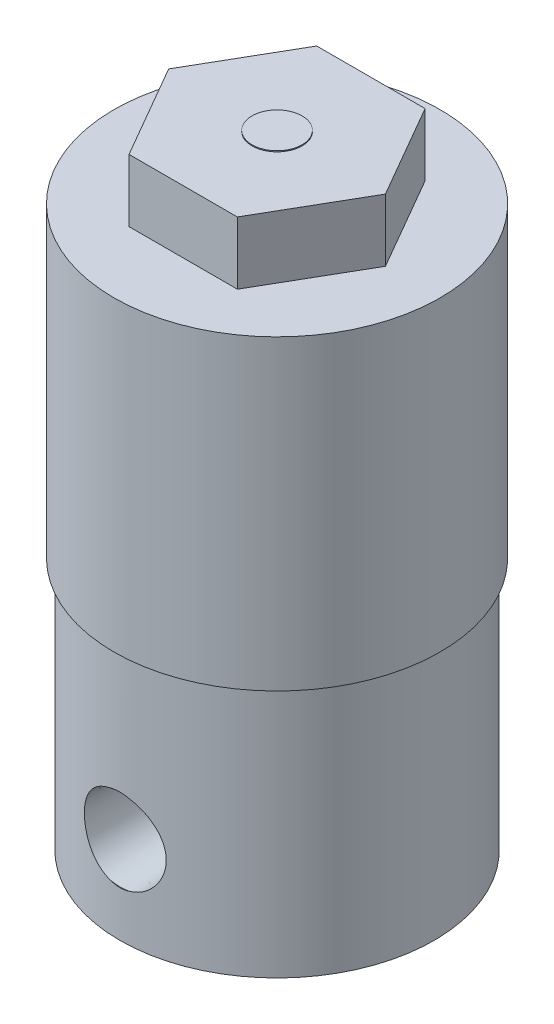
SolidWorks part; units mm, degrees
ref_plane "Plan de face" through (0, 0, 0) normal (0, 0, 1) x (1, 0, 0)
ref_plane "Plan de dessus" through (0, 0, 0) normal (0, 1, 0) x (1, 0, 0)
ref_plane "Plan de droite" through (0, 0, 0) normal (1, 0, 0) x (0, 0, -1)
sketch "Esquisse1" plane through (0, 0, 0) normal (0, 1, 0) x (1, 0, 0)
  circle A0 centre (0, 0) radius 12.56
extrude "Boss.-Extru.1" add sketch "Esquisse1" along normal blind 20.19 contours A0
ref_plane "Plan1" through (0, 0, 12.56) normal (0, 0, 1) x (1, 0, 0)
hole_wizard "Trou taraudé 1/8 Rc1" positions "Esquisse8" profile "Esquisse9" size "1/8" standard "KS"
sketch "Esquisse8" plane through (0, 0, 12.56) normal (0, 0, 1) x (1, 0, 0)
  line L0 (0, -11.1045) -> (0, 11.1045) construction
  line L1 (13.816, 0) -> (-13.816, 0) construction
  point P0 (0, 6.96)
  dimension "D1" = 6.96
sketch "Esquisse9" plane through (0, 6.96, 12.56) normal (1, 0, 0) x (0, -1, 0)
  line L0 (0, 0) -> (0, 10.8734)
  line L1 (3.95, 8.5) -> (0, 10.8734)
  line L2 (-3.95, 8.5) -> (0, 10.8734) construction
  line L3 (3.95, 8.5) -> (3.95, 7.4)
  line L4 (3.95, 7.4) -> (3.0528, 7.4)
  line L5 (3.0528, 7.4) -> (3.283, 0.025)
  line L6 (3.283, 0.025) -> (3.308, 0)
  line L7 (3.308, 0) -> (0, 0)
  line L8 (0, -6.35) -> (0, 107.95) construction
  line L9 (-3.283, 0.025) -> (-3.308, 0) construction
  line L11 (-3.95, 7.4) -> (-3.0528, 7.4) construction
  line L12 (-3.0528, 7.4) -> (-3.283, 0.025) construction
  dimension "Diamètre du trou pour taraudage" = 7.9
  dimension "Profondeur du trou pour taraudage" = 8.5
  dimension "Diamètre du filetage" = 6.566
  dimension "Angle de filetage" = 3.576
  dimension "Profondeur du filetage" = 7.4
  dimension "Diamètre du fraisage" = 6.616
  dimension "Angle du fraisage" = 90
  dimension "Angle de pointe" = 118
hole_wizard "Trou taraudé 1/8 Rc2" positions "Esquisse3D1" profile "Esquisse12" size "1/8" standard "KS"
sketch3d "Esquisse3D1"
  point P0 (0, 6.9496, -12.56)
sketch "Esquisse12" plane through (0, 6.9496, -12.56) normal (1, 0, 0) x (0, 1, 0)
  line L0 (0, 0) -> (0, 10.8734)
  line L1 (3.95, 8.5) -> (0, 10.8734)
  line L2 (-3.95, 8.5) -> (0, 10.8734) construction
  line L3 (3.95, 8.5) -> (3.95, 7.4)
  line L4 (3.95, 7.4) -> (3.0528, 7.4)
  line L5 (3.0528, 7.4) -> (3.283, 0.025)
  line L6 (3.283, 0.025) -> (3.308, 0)
  line L7 (3.308, 0) -> (0, 0)
  line L8 (0, -6.35) -> (0, 107.95) construction
  line L9 (-3.283, 0.025) -> (-3.308, 0) construction
  line L11 (-3.95, 7.4) -> (-3.0528, 7.4) construction
  line L12 (-3.0528, 7.4) -> (-3.283, 0.025) construction
  dimension "Diamètre du trou pour taraudage" = 7.9
  dimension "Profondeur du trou pour taraudage" = 8.5
  dimension "Diamètre du filetage" = 6.566
  dimension "Angle de filetage" = 3.576
  dimension "Profondeur du filetage" = 7.4
  dimension "Diamètre du fraisage" = 6.616
  dimension "Angle du fraisage" = 90
  dimension "Angle de pointe" = 118
sketch "Esquisse13" plane through (0, 20.19, 0) normal (0, 1, 0) x (1, 0, 0)
  circle A0 centre (0, 0) radius 2
  dimension "D1" = 4
extrude "Boss.-Extru.2" add sketch "Esquisse13" along normal blind 29.59
sketch "Esquisse14" plane through (0, 20.19, 0) normal (0, 1, 0) x (1, 0, 0)
  circle A0 centre (0, 0) radius 13.03
  dimension "D1" = 26.06
extrude "Boss.-Extru.3" add sketch "Esquisse14" along normal blind 24.51
sketch "Esquisse16" plane through (0, 44.7, 0) normal (0, 1, 0) x (1, 0, 0)
  line L1 (8.6603, 0) -> (4.3301, 7.5)
  line L2 (4.3301, 7.5) -> (-4.3301, 7.5)
  line L3 (-4.3301, 7.5) -> (-8.6603, 0)
  line L4 (-8.6603, 0) -> (-4.3301, -7.5)
  line L5 (-4.3301, -7.5) -> (4.3301, -7.5)
  line L6 (4.3301, -7.5) -> (8.6603, 0)
  circle A0 centre (0, 0) radius 7.5 construction
  dimension "D1" = 15
extrude "Boss.-Extru.4" add sketch "Esquisse16" along normal blind 5
sketch "Esquisse17" plane through (0, 0, 0) normal (0, -1, 0) x (1, 0, 0)
  line L0 (14.333, 0) -> (-14.333, 0) construction
  circle A0 centre (-9.335, 0) radius 0.5
  circle A1 centre (9.335, 0) radius 0.5
  point P6 (0, 0)
  point P8 (0, 0)
  point P9 (0, 0)
  point P10 (0, 0)
  point P11 (0, 0)
  dimension "D3" = 1
  dimension "D4" = 1
  dimension "D1" = 9.335
  dimension "D2" = 9.335
hole_wizard "Dégagement #81" positions "Esquisse3D2" profile "Esquisse18" hole size "#8" standard "Ansi Inch"
sketch3d "Esquisse3D2"
  point P0 (-9.335, 0, 0)
  point P3 (9.335, 0, 0)
sketch "Esquisse18" plane through (-9.335, 0, 0) normal (1, 0, 0) x (0, 0, -1)
  line L0 (0, 0) -> (0, 10)
  line L1 (0, 10) -> (2.2479, 8.6493)
  line L2 (2.2479, 8.6493) -> (2.2479, 0.635)
  line L3 (2.2479, 0.635) -> (2.8829, 0)
  line L5 (2.8829, 0) -> (0, 0)
  line L6 (-2.2479, 0.635) -> (-2.8829, 0) construction
  line L10 (0, 10) -> (-2.2479, 8.6493) construction
  line L11 (0, -6.35) -> (0, 107.95) construction
  dimension "Diamètre du perçage" = 4.4958
  dimension "Profondeur du perçage" = 10
  dimension "Diamètre du fraisage entrant" = 5.7658
  dimension "Angle du fraisage entrant" = 90
  dimension "Angle de pointe" = 118
